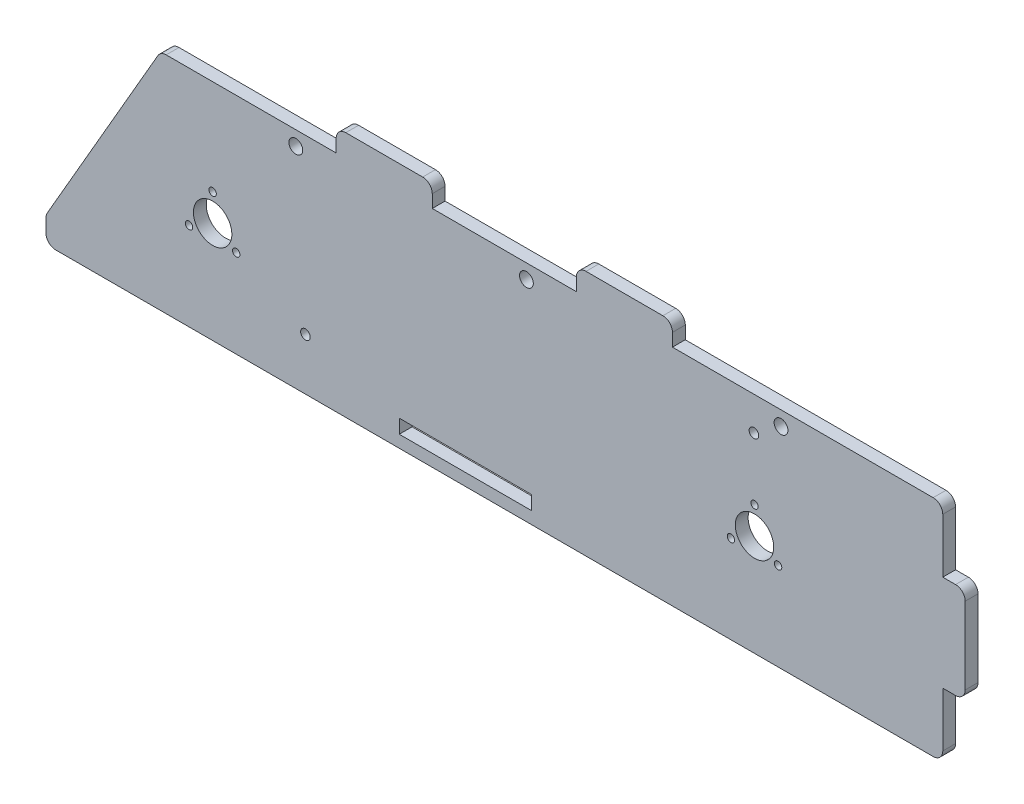
SolidWorks part; units mm, degrees
ref_plane "Front Plane" through (0, 0, 0) normal (0, 0, 1) x (1, 0, 0)
ref_plane "Top Plane" through (0, 0, 0) normal (0, 1, 0) x (1, 0, 0)
ref_plane "Right Plane" through (0, 0, 0) normal (1, 0, 0) x (0, 0, -1)
sketch "Sketch1" plane through (0, 0, 0) normal (0, 0, 1) x (1, 0, 0)
  line L0 (-128.1718, -30) -> (151.8282, -30)
  line L1 (-128.1718, -30) -> (-128.1718, -22)
  line L2 (-128.1718, -22) -> (-92.376, 40)
  line L5 (-37.566, 40) -> (-37.566, 47)
  line L6 (-37.566, 47) -> (-7.566, 47)
  line L7 (-7.566, 47) -> (-7.566, 40)
  line L8 (37.434, 40) -> (37.434, 47)
  line L9 (37.434, 47) -> (67.434, 47)
  line L10 (67.434, 47) -> (67.434, 40)
  line L11 (-92.376, 40) -> (-37.566, 40)
  line L12 (-7.566, 40) -> (37.434, 40)
  line L13 (67.434, 40) -> (151.8282, 40)
  line L16 (158.8282, 5) -> (158.8282, 20)
  line L17 (158.8282, 5) -> (158.8282, -10)
  line L18 (158.8282, -10) -> (151.8282, -10)
  line L19 (158.8282, 20) -> (151.8282, 20)
  line L20 (151.8282, 40) -> (151.8282, 20)
  line L21 (151.8282, -10) -> (151.8282, -30)
  line L22 (-17.8718, -21.85) -> (23.4282, -21.85)
  line L23 (-17.8718, -21.85) -> (-17.8718, -26.2)
  line L24 (-17.8718, -26.2) -> (23.4282, -26.2)
  line L25 (23.4282, -21.85) -> (23.4282, -26.2)
  circle A0 centre (-76.141, 1.72) radius 6
  circle A3 centre (-76.141, 1.72) radius 8.5 construction
  circle A4 centre (-76.141, 10.22) radius 1.15
  circle A5 centre (-68.7797, -2.53) radius 1.15
  circle A6 centre (-83.5022, -2.53) radius 1.15
  circle A7 centre (93.0482, 1.72) radius 6
  circle A8 centre (93.0482, 1.72) radius 8.5 construction
  circle A9 centre (93.0482, 10.22) radius 1.15
  circle A10 centre (100.4095, -2.53) radius 1.15
  circle A11 centre (85.687, -2.53) radius 1.15
  circle A12 centre (92.8604, 29.5) radius 1.5
  circle A13 centre (-50.1718, 35.5) radius 2.15
  circle A14 centre (21.8282, 35.5) radius 2.15
  circle A15 centre (101.3282, 35.5) radius 2.15
  circle A16 centre (-47.1718, -13.85) radius 1.5
  point P39 (151.8282, 30)
  dimension "D22" = 12
  dimension "D23" = 31.72
  dimension "D24" = 33.2
  dimension "D25" = 2.3
  dimension "D26" = 17
  dimension "D28" = 12
  dimension "D29" = 17
  dimension "D30" = 65.78
  dimension "D31" = 31.72
  dimension "D32" = 2.3
  dimension "D34" = 3
  dimension "D35" = 10.5
  dimension "D36" = 58.97
  dimension "D39" = 4.3
  dimension "D40" = 4.5
  dimension "D41" = 130
  dimension "D42" = 4.5
  dimension "D43" = 202
  dimension "D44" = 4.3
  dimension "D45" = 4.3
  dimension "D46" = 4.5
  dimension "D47" = 50.5
  dimension "D48" = 3
  dimension "D49" = 16.15
  dimension "D1" = 280
  dimension "D2" = 8
  dimension "D3" = 70
  dimension "D4" = 60
  dimension "D5" = 30
  dimension "D6" = 7
  dimension "D7" = 30
  dimension "D8" = 54.81
  dimension "D9" = 45
  dimension "D10" = 70
  dimension "D11" = 15
  dimension "D12" = 15
  dimension "D13" = 7
  dimension "D14" = 30
  dimension "D15" = 100
  dimension "D16" = 40
  dimension "D17" = 47
  dimension "D18" = 151.8282
  dimension "D19" = 20
  dimension "D20" = 41.3
  dimension "D21" = 4.35
  dimension "D37" = 3.8
  dimension "D38" = 110.3
  dimension "D50" = 199
  dimension "D27" = 3
  dimension "D33" = 3
extrude "Boss-Extrude1" add sketch "Sketch1" along normal blind 4
fillet "Fillet1" radius 3 11 edges at (-128.1718, -30, 2) (-128.1718, -22, 2) (-92.376, 40, 2) (-37.566, 47, 2) (-7.566, 47, 2) (37.434, 47, 2) (67.434, 47, 2) (151.8282, -30, 2) (158.8282, -10, 2) (158.8282, 20, 2) (151.8282, 40, 2)
